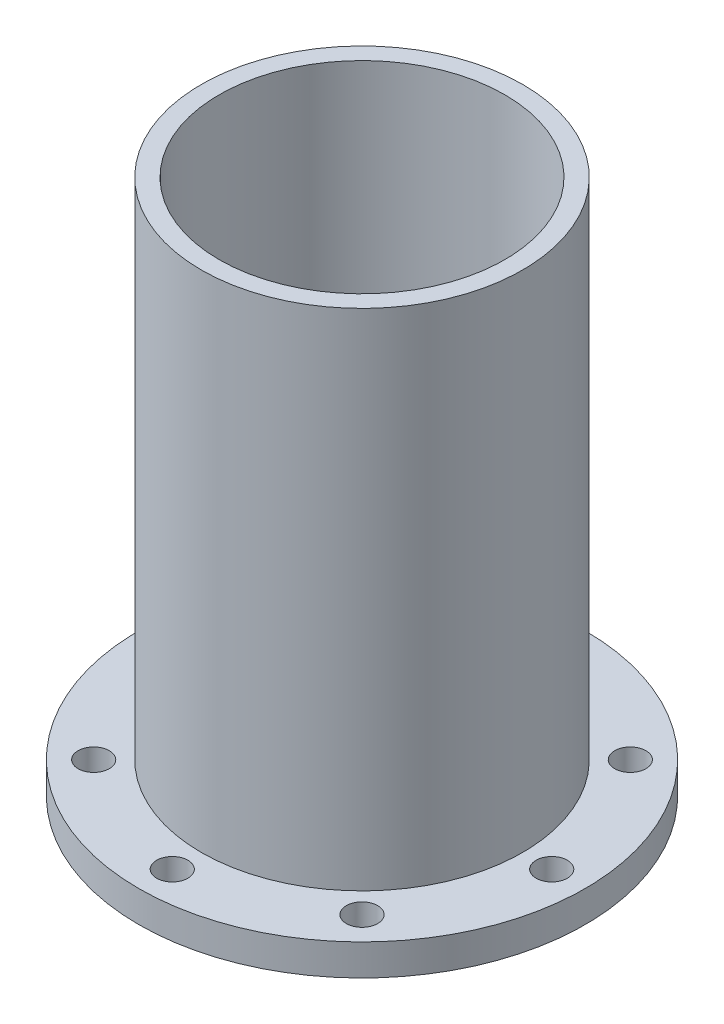
SolidWorks part; units mm, degrees
ref_plane "Front Plane" through (0, 0, 0) normal (0, 0, 1) x (1, 0, 0)
ref_plane "Top Plane" through (0, 0, 0) normal (0, 1, 0) x (1, 0, 0)
ref_plane "Right Plane" through (0, 0, 0) normal (1, 0, 0) x (0, 0, -1)
sketch "Sketch1" plane through (0, 0, 0) normal (0, 0, 1) x (1, 0, 0)
  line L0 (0, 40.25) -> (0, -41.65) construction
  line L1 (-18, 30) -> (-18, -26.5)
  line L2 (-16, -30) -> (-16, 30)
  line L3 (-16, -30) -> (-25, -30)
  line L4 (-25, -30) -> (-25, -26.5)
  line L5 (-25, -26.5) -> (-18, -26.5)
  line L6 (-16, 30) -> (-18, 30)
  point P7 (-16, 0)
  dimension "D1" = 36
  dimension "D2" = 32
  dimension "D3" = 50
  dimension "D4" = 3.5
  dimension "D5" = 60
revolve "Revolve1" add sketch "Sketch1" angle 360 about L0
sketch "Sketch2" plane through (0, -26.5, 0) normal (0, 1, 0) x (1, 0, 0)
  line L0 (0, 0) -> (-15.026, 15.026) construction
  line L1 (0, 0) -> (0, 21.25) construction
  circle A0 centre (0, 0) radius 21.25 construction
  circle A1 centre (0, 21.25) radius 1.75
  circle A2 centre (15.026, 15.026) radius 1.75
  circle A3 centre (21.25, 0) radius 1.75
  circle A4 centre (15.026, -15.026) radius 1.75
  circle A5 centre (0, -21.25) radius 1.75
  circle A6 centre (-15.026, -15.026) radius 1.75
  circle A7 centre (-21.25, 0) radius 1.75
  circle A8 centre (-15.026, 15.026) radius 1.75
  point P21 (0, 0)
  dimension "D1" = 42.5
  dimension "D2" = 3.5
  dimension "D4" = 45
  dimension "D3" = 8
extrude "Cut-Extrude1" cut sketch "Sketch2" against normal blind 10
